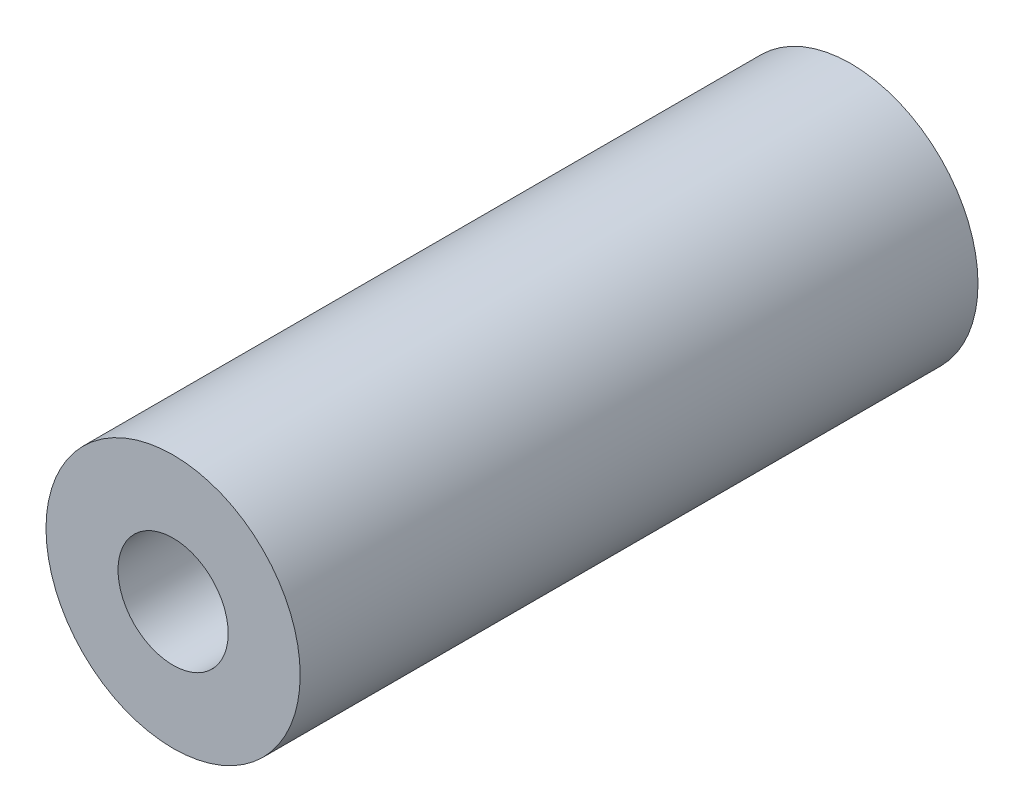
SolidWorks part; units mm, degrees
ref_plane "Front Plane" through (0, 0, 0) normal (0, 0, 1) x (1, 0, 0)
ref_plane "Top Plane" through (0, 0, 0) normal (0, 1, 0) x (1, 0, 0)
ref_plane "Right Plane" through (0, 0, 0) normal (1, 0, 0) x (0, 0, -1)
sketch "Sketch1" plane through (0, 0, 0) normal (0, 0, 1) x (1, 0, 0)
  circle A0 centre (0, 0) radius 9.525 construction
  circle A1 centre (0, 0) radius 4.1275 construction
  point P4 (0, 9.525)
  dimension "OD" = 19.05
  dimension "ID" = 8.255
sketch "Sketch2" plane through (0, 0, 0) normal (1, 0, 0) x (0, 0, -1)
  line L0 (-25.4, 9.525) -> (25.4, 9.525) construction
  dimension "Length" = 50.8
sketch "Sketch3" plane through (0, 0, 0) normal (0, 0, 1) x (1, 0, 0)
  circle A0 centre (0, 0) radius 4.1275 construction
  circle A1 centre (0, 0) radius 9.525 construction
  circle A2 centre (0, 0) radius 4.1275
  circle A3 centre (0, 0) radius 9.525
extrude "Boss-Extrude1" add sketch "Sketch3" against normal up to vertex (25.4 mm away) and the other way up to vertex (25.4 mm away) up to point (0, 9.525, -25.4) other way up to point (0, 9.525, 25.4)
